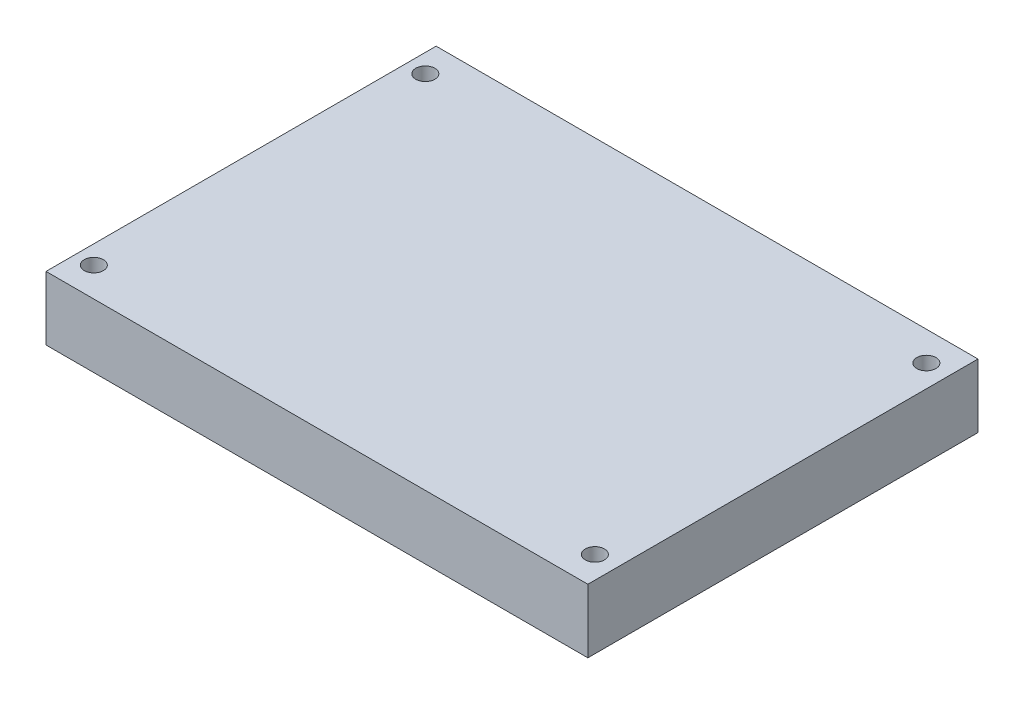
SolidWorks part; units mm, degrees
ref_plane "前视基准面" through (0, 0, 0) normal (0, 0, 1) x (1, 0, 0)
ref_plane "上视基准面" through (0, 0, 0) normal (0, 1, 0) x (1, 0, 0)
ref_plane "右视基准面" through (0, 0, 0) normal (1, 0, 0) x (0, 0, -1)
sketch "草图1" plane through (0, 0, 0) normal (0, 1, 0) x (1, 0, 0)
  line L0 (-42.5, 0) -> (42.5, 0) construction
  line L1 (-42.5, 30.6) -> (42.5, 30.6)
  line L2 (-42.5, 30.6) -> (-42.5, -30.6)
  line L3 (-42.5, -30.6) -> (42.5, -30.6)
  line L4 (42.5, 30.6) -> (42.5, -30.6)
  line L5 (-42.5, 30.6) -> (42.5, -30.6) construction
  line L6 (-42.5, -30.6) -> (42.5, 30.6) construction
  circle A0 centre (-39.6, 26) radius 1.5
  circle A1 centre (39, 26) radius 1.5
  circle A2 centre (39, -26) radius 1.5
  circle A3 centre (-39.6, -26) radius 1.5
  point P0 (0, 0)
  point P18 (-38.9858, -24.6315)
  dimension "D4" = 3
  dimension "D6" = 3
  dimension "D1" = 85
  dimension "D2" = 61.2
  dimension "D3" = 2.9
  dimension "D5" = 3.5
  dimension "D7" = 4.6
  dimension "D8" = 78.6
  dimension "D9" = 52
  dimension "D10" = 52
extrude "凸台-拉伸1" add sketch "草图1" along normal blind 10
